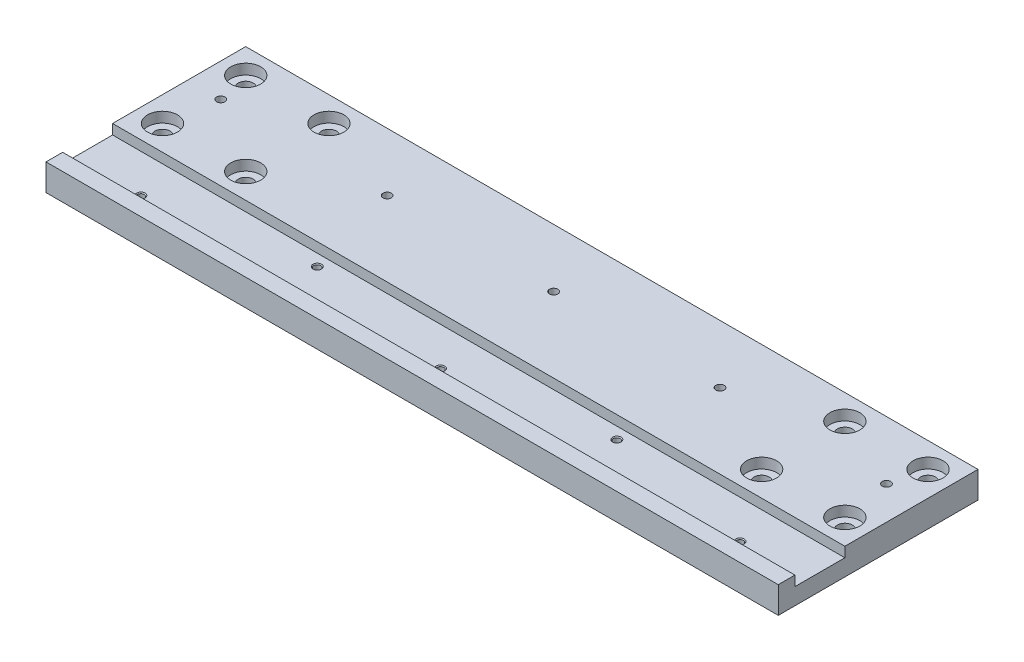
SolidWorks part; units mm, degrees
ref_plane "Front Plane" through (0, 0, 0) normal (0, 0, 1) x (1, 0, 0)
ref_plane "Top Plane" through (0, 0, 0) normal (0, 1, 0) x (1, 0, 0)
ref_plane "Right Plane" through (0, 0, 0) normal (1, 0, 0) x (0, 0, -1)
sketch "Skizze1" plane through (0, 0, 0) normal (0, 1, 0) x (1, 0, 0)
  line L1 (-110, 30) -> (110, 30)
  line L2 (-110, 30) -> (-110, -30)
  line L3 (-110, -30) -> (110, -30)
  line L4 (110, 30) -> (110, -30)
  line L5 (0, -30) -> (0, 30) construction
  line L6 (-110, 0) -> (110, 0) construction
  point P48 (0, 0)
  dimension "D1" = 220
  dimension "D2" = 60
extrude "Aufsatz-Linear austragen1" add sketch "Skizze1" along normal blind 8
hole_wizard "Stirnsenkung für M4 Flachkopfschraube mit Schlitz1" positions "Skizze2" profile "Skizze3" counterbore size "M4" standard "DIN"
sketch "Skizze2" plane through (0, 8, 0) normal (0, 1, 0) x (1, 0, 0)
  line L0 (-110, 10) -> (110, 10) construction
  line L1 (-110, 30) -> (-110, -30) construction
  line L5 (0, 30) -> (0, -30) construction
  line L6 (110, 30) -> (-110, 30) construction
  line L7 (-110, -30) -> (110, -30) construction
  line L8 (-77.5, 22.5) -> (-102.5, 22.5) construction
  line L9 (-90, 22.5) -> (-90, -30) construction
  line L10 (110, -30) -> (110, 30) construction
  point P0 (-102.5, 22.5)
  point P22 (-77.5, 22.5)
  point P38 (-77.5, -2.5)
  point P40 (-102.5, -2.5)
  point P41 (102.5, -2.5)
  point P42 (77.5, -2.5)
  point P43 (77.5, 22.5)
  point P44 (102.5, 22.5)
  dimension "D1" = 25
  dimension "D2" = 25
  dimension "D3" = 20
  dimension "D4" = 20
sketch "Skizze3" plane through (-102.5, 8, -22.5) normal (1, 0, 0) x (0, 0, 1)
  line L0 (0, 0) -> (0, 12.8519)
  line L1 (0, 12.8519) -> (2.25, 11.5)
  line L2 (2.25, 11.5) -> (2.25, 3.1)
  line L3 (2.25, 3.1) -> (4.5, 3.1)
  line L4 (4.5, 3.1) -> (4.5, 0)
  line L5 (4.5, 0) -> (0, 0)
  line L10 (0, 12.8519) -> (-2.25, 11.5) construction
  line L11 (0, -6.35) -> (0, 107.95) construction
  dimension "Bohrerdurchmesser" = 4.5
  dimension "Bohrungstiefe" = 11.5
  dimension "Senkdurchmesser2" = 9
  dimension "Senktiefe2" = 3.1
  dimension "Spitzenwinkel" = 118
hole_wizard "M3 Gewindebohrung1" positions "Skizze6" profile "Skizze7" tap size "M3" standard "DIN"
sketch "Skizze6" plane through (0, 8, 0) normal (0, 1, 0) x (1, 0, 0)
  line L5 (0, 30) -> (0, -30) construction
  line L6 (110, 30) -> (-110, 30) construction
  line L7 (-110, -30) -> (110, -30) construction
  line L9 (-110, 12.5) -> (110, 12.5) construction
  line L10 (-110, 30) -> (-110, -30) construction
  line L11 (110, -30) -> (110, 30) construction
  point P104 (0, 12.5)
  point P110 (50, 12.5)
  point P111 (100, 12.5)
  point P117 (-100, 12.5)
  point P118 (-50, 12.5)
  point P124 (150, 12.5) [skipped]
  point P126 (200, 12.5) [skipped]
  dimension "D3" = 50
  dimension "D1" = 17.5
  dimension "D2" = 5
sketch "Skizze7" plane through (-50, 8, -12.5) normal (1, 0, 0) x (0, 0, 1)
  line L0 (0, 0) -> (0, 9.2511)
  line L1 (0, 9.2511) -> (1.25, 8.5)
  line L2 (1.25, 8.5) -> (1.25, 0)
  line L5 (1.25, 0) -> (0, 0)
  line L10 (0, 9.2511) -> (-1.25, 8.5) construction
  line L11 (0, -6.35) -> (0, 107.95) construction
  dimension "Bohrerdurchmesser" = 2.5
  dimension "Bohrungstiefe" = 8.5
  dimension "Spitzenwinkel" = 118
cosmetic thread "Bohrungsgewinde1" parameters "D1"=6, "D2"=3
cosmetic thread "Bohrungsgewinde2" parameters "D1"=6, "D2"=3
cosmetic thread "Bohrungsgewinde7" parameters "D1"=6, "D2"=3
cosmetic thread "Bohrungsgewinde8" parameters "D1"=6, "D2"=3
cosmetic thread "Bohrungsgewinde9" parameters "D1"=6, "D2"=3
sketch "Skizze8" plane through (-110, 0, 0) normal (-1, 0, 0) x (0, 0, 1)
  line L0 (-30, 8) -> (30, 8) construction
  line L1 (10, 8) -> (25, 8)
  line L2 (10, 8) -> (10, 5)
  line L3 (10, 5) -> (25, 5)
  line L4 (25, 8) -> (25, 5)
  line L5 (17.5, 5) -> (17.5, 8) construction
  line L6 (10, 6.5) -> (25, 6.5) construction
  line L7 (30, 8) -> (30, 0) construction
  point P108 (17.5, 6.5)
  dimension "D1" = 3
  dimension "D2" = 15
  dimension "D3" = 5
extrude "Schnitt-Linear austragen1" cut sketch "Skizze8" against normal through all
hole_wizard "M2.5 Gewindebohrung1" positions "Skizze9" profile "Skizze10" tap size "M2.5" standard "DIN" end condition through all
sketch "Skizze9" plane through (0, 5, 0) normal (0, 1, 0) x (1, 0, 0)
  line L0 (-110, -17.5) -> (110, -17.5) construction
  line L1 (-110, -10) -> (-110, -25) construction
  line L2 (110, -10) -> (110, -25) construction
  line L4 (-110, -13.5) -> (110, -13.5) construction
  line L7 (110, -21.5) -> (-110, -21.5) construction
  line L9 (0, -10) -> (0, -25) construction
  line L10 (110, -10) -> (-110, -10) construction
  line L11 (110, -25) -> (-110, -25) construction
  point P0 (-90, -21.5)
  point P30 (0, -21.5)
  point P32 (90, -21.5)
  point P34 (45, -13.5)
  point P36 (-45, -13.5)
  dimension "D1" = 8
  dimension "D2" = 4
  dimension "D3" = 90
  dimension "D4" = 180
sketch "Skizze10" plane through (-90, 5, 21.5) normal (1, 0, 0) x (0, 0, 1)
  line L0 (0, 0) -> (0, 5)
  line L1 (0, 5) -> (1.025, 5)
  line L2 (1.025, 5) -> (1.025, 0.25)
  line L3 (1.025, 0.25) -> (1.275, 0)
  line L5 (1.275, 0) -> (0, 0)
  line L6 (-1.025, 0.25) -> (-1.275, 0) construction
  line L11 (0, -6.35) -> (0, 107.95) construction
  dimension "Bohrerdurchmesser" = 2.05
  dimension "Bohrungstiefe" = 5
  dimension "Senkdurchmesser (Oben)" = 2.55
  dimension "Senkwinkel (Oben)" = 90
cosmetic thread "Bohrungsgewinde17" parameters "D2"=2.5
cosmetic thread "Bohrungsgewinde18" parameters "D2"=2.5
cosmetic thread "Bohrungsgewinde19" parameters "D2"=2.5
cosmetic thread "Bohrungsgewinde20" parameters "D2"=2.5
cosmetic thread "Bohrungsgewinde21" parameters "D2"=2.5
